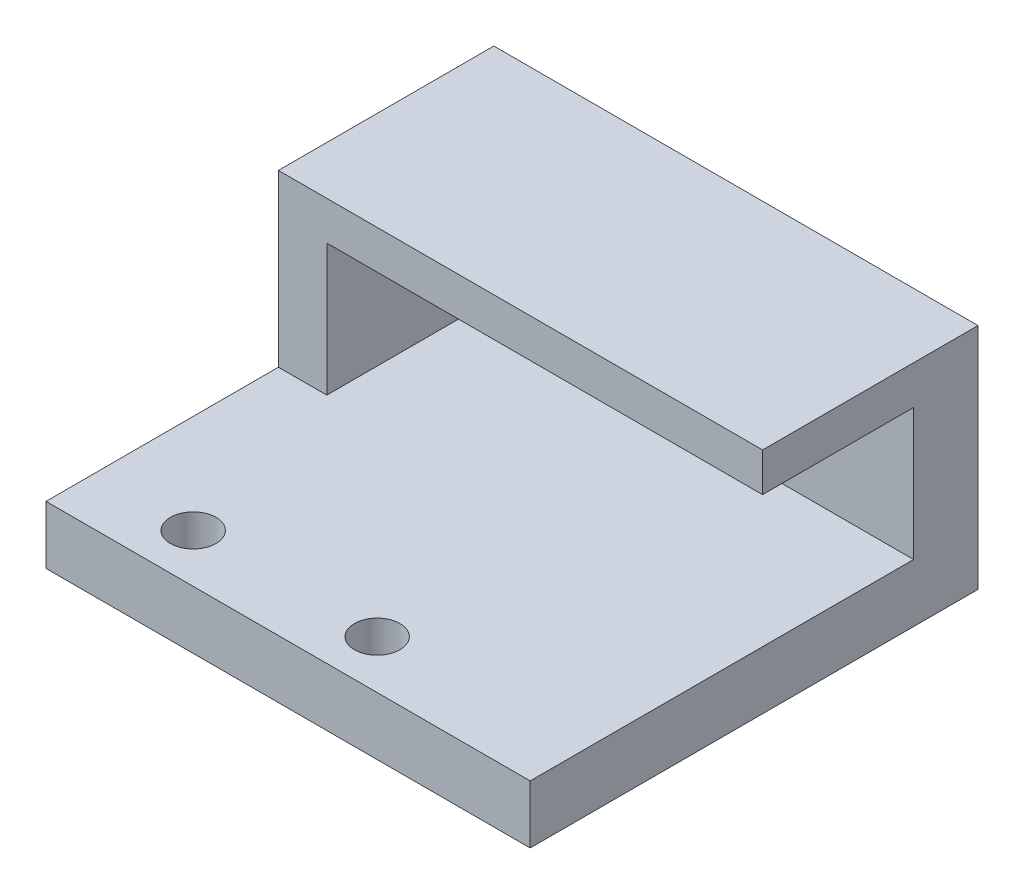
SolidWorks part; units mm, degrees
ref_plane "Front Plane" through (0, 0, 0) normal (0, 0, 1) x (1, 0, 0)
ref_plane "Top Plane" through (0, 0, 0) normal (0, 1, 0) x (1, 0, 0)
ref_plane "Right Plane" through (0, 0, 0) normal (1, 0, 0) x (0, 0, -1)
sketch "Sketch1" plane through (0, 0, 0) normal (0, 1, 0) x (1, 0, 0)
  line L1 (0, 0) -> (25, 0)
  line L2 (0, 0) -> (0, 20)
  line L3 (0, 20) -> (25, 20)
  line L4 (25, 0) -> (25, 20)
  circle A0 centre (5.1, 2.5) radius 1.175
  circle A1 centre (14.6, 2.5) radius 1.175
  dimension "D3" = 2.35
  dimension "D4" = 2.35
  dimension "D1" = 20
  dimension "D2" = 25
  dimension "D5" = 5.1
  dimension "D6" = 9.5
  dimension "D7" = 2.5
extrude "Boss-Extrude2" add sketch "Sketch1" along normal blind 3
sketch "Sketch3" plane through (0, 3, 0) normal (0, 1, 0) x (1, 0, 0)
  line L1 (0, 20) -> (2.5, 20)
  line L2 (0, 20) -> (0, 12)
  line L3 (0, 12) -> (2.5, 12)
  line L4 (2.5, 20) -> (2.5, 12)
  dimension "D1" = 2.5
  dimension "D2" = 8
extrude "Boss-Extrude3" add sketch "Sketch3" along normal blind 6.8
sketch "Sketch5" plane through (0, 0, -20) normal (0, 0, -1) x (-1, 0, 0)
  line L1 (0, 9.8) -> (-2.5, 9.8)
  line L2 (0, 9.8) -> (0, 3)
  line L3 (0, 3) -> (-2.5, 3)
  line L4 (-2.5, 9.8) -> (-2.5, 3)
  line L10 (-25, 0) -> (0, 0)
  line L11 (0, 0) -> (0, 9.8)
  line L12 (0, 9.8) -> (-2.5, 9.8)
  line L13 (-2.5, 9.8) -> (-2.5, 3)
  line L14 (-2.5, 3) -> (-25, 3)
  line L15 (-25, 3) -> (-25, 0)
  line L16 (-25, 0) -> (0, 0)
  line L17 (0, 0) -> (0, 9.8)
  line L18 (0, 9.8) -> (-2.5, 9.8)
  line L19 (-2.5, 9.8) -> (-2.5, 3)
  line L20 (-2.5, 3) -> (-25, 3)
  line L21 (-25, 3) -> (-25, 0)
  line M7 (-25, 0) -> (0, 0)
  line M8 (0, 0) -> (0, 9.8)
  line M9 (0, 9.8) -> (-2.5, 9.8)
  line M10 (-2.5, 9.8) -> (-2.5, 3)
  line M11 (-2.5, 3) -> (-25, 3)
  line M12 (-25, 3) -> (-25, 0)
  dimension "D1" = 0
sketch "Sketch7" plane through (0, 0, 0) normal (-1, 0, 0) x (0, 0, 1)
  line L0 (-20, 9.8) -> (-20, 0) construction
  line L1 (-20, 9.8) -> (-12, 3) construction
  line L2 (-12, 3) -> (-20, 3) construction
  line L3 (-20, 3) -> (-12, 9.8) construction
  circle A0 centre (-18, 6.4) radius 1.8
  dimension "D1" = 3.6
  dimension "D2" = 2
extrude "Boss-Extrude5" add sketch "Sketch5" along normal blind 6.8 contours L3 M8 M11 M12 M7 | L3 M8 M9 M10
extrude "Cut-Extrude1" cut sketch "Sketch7" against normal blind 6.8
sketch "Sketch8" plane through (2.5, 0, 0) normal (1, 0, 0) x (0, 0, -1)
  line L0 (12, 3) -> (26.8, 3) construction
  line L1 (26.8, 9.8) -> (19.8, 9.8)
  line L2 (26.8, 9.8) -> (26.8, 3)
  line L3 (26.8, 3) -> (19.8, 3)
  line L4 (19.8, 9.8) -> (19.8, 3)
extrude "Boss-Extrude6" add sketch "Sketch8" along normal up to surface (22.5 mm away) up to face at (25, 1.5, -13.4)
sketch "Sketch9" plane through (0, 9.8, 0) normal (0, 1, 0) x (1, 0, 0)
  line L1 (0, 12) -> (25, 12)
  line L2 (0, 12) -> (0, 26.8)
  line L3 (0, 26.8) -> (25, 26.8)
  line L4 (25, 12) -> (25, 26.8)
extrude "Boss-Extrude7" add sketch "Sketch9" along normal blind 2
sketch "Sketch10" plane through (25, 0, 0) normal (1, 0, 0) x (0, 0, -1)
  line L0 (0, 0) -> (26.8, 0) construction
  line L1 (26.8, 11.8) -> (23.124, 11.8)
  line L2 (26.8, 11.8) -> (26.8, 0)
  line L3 (26.8, 0) -> (23.124, 0)
  line L4 (23.124, 11.8) -> (23.124, 0)
extrude "Cut-Extrude2" cut sketch "Sketch10" against normal blind 36
